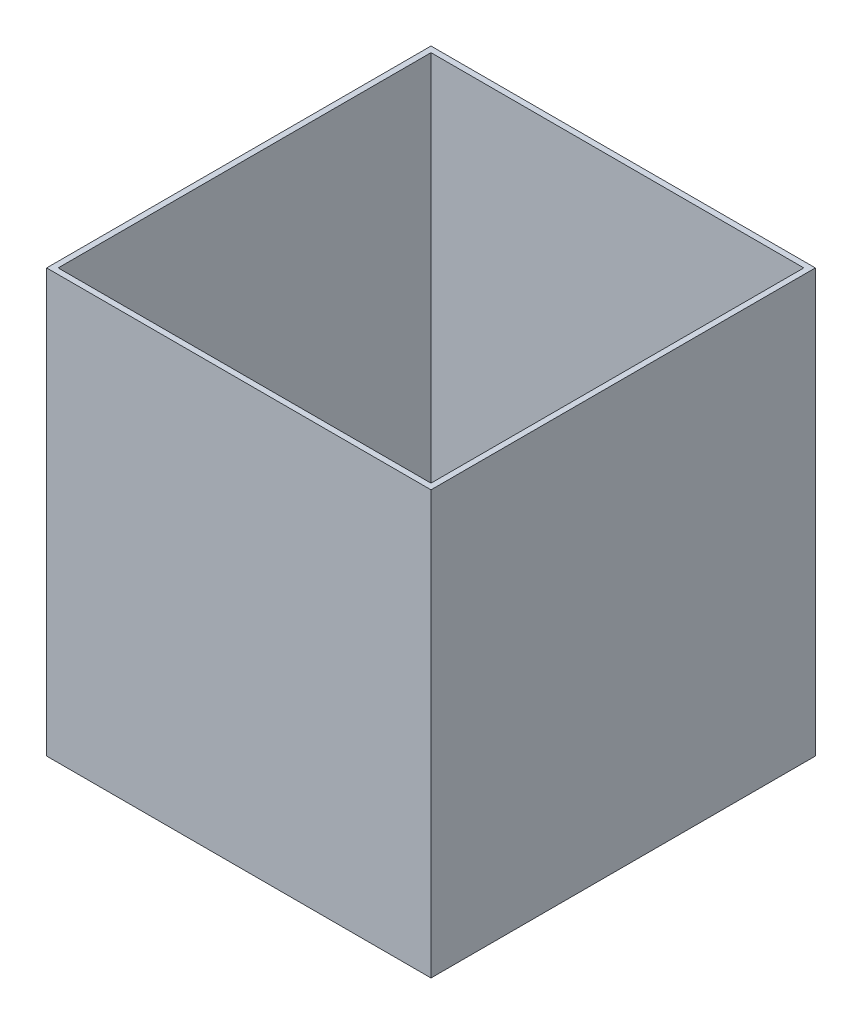
SolidWorks part; units mm, degrees
ref_plane "前视基准面" through (0, 0, 0) normal (0, 0, 1) x (1, 0, 0)
ref_plane "上视基准面" through (0, 0, 0) normal (0, 1, 0) x (1, 0, 0)
ref_plane "右视基准面" through (0, 0, 0) normal (1, 0, 0) x (0, 0, -1)
sketch "草图1" plane through (0, 0, 0) normal (0, 1, 0) x (1, 0, 0)
  line L1 (0, 0) -> (-200, 0)
  line L2 (0, 0) -> (0, 200)
  line L3 (0, 200) -> (-200, 200)
  line L4 (-200, 0) -> (-200, 200)
  line L5 (-197, 197) -> (-3, 197)
  line L6 (-197, 197) -> (-197, 3)
  line L7 (-197, 3) -> (-3, 3)
  line L8 (-3, 197) -> (-3, 3)
  dimension "D1" = 200
  dimension "D2" = 200
  dimension "D3" = 194
  dimension "D4" = 194
  dimension "D5" = 3
  dimension "D6" = 3
extrude "凸台-拉伸1" add sketch "草图1" along normal blind 220
